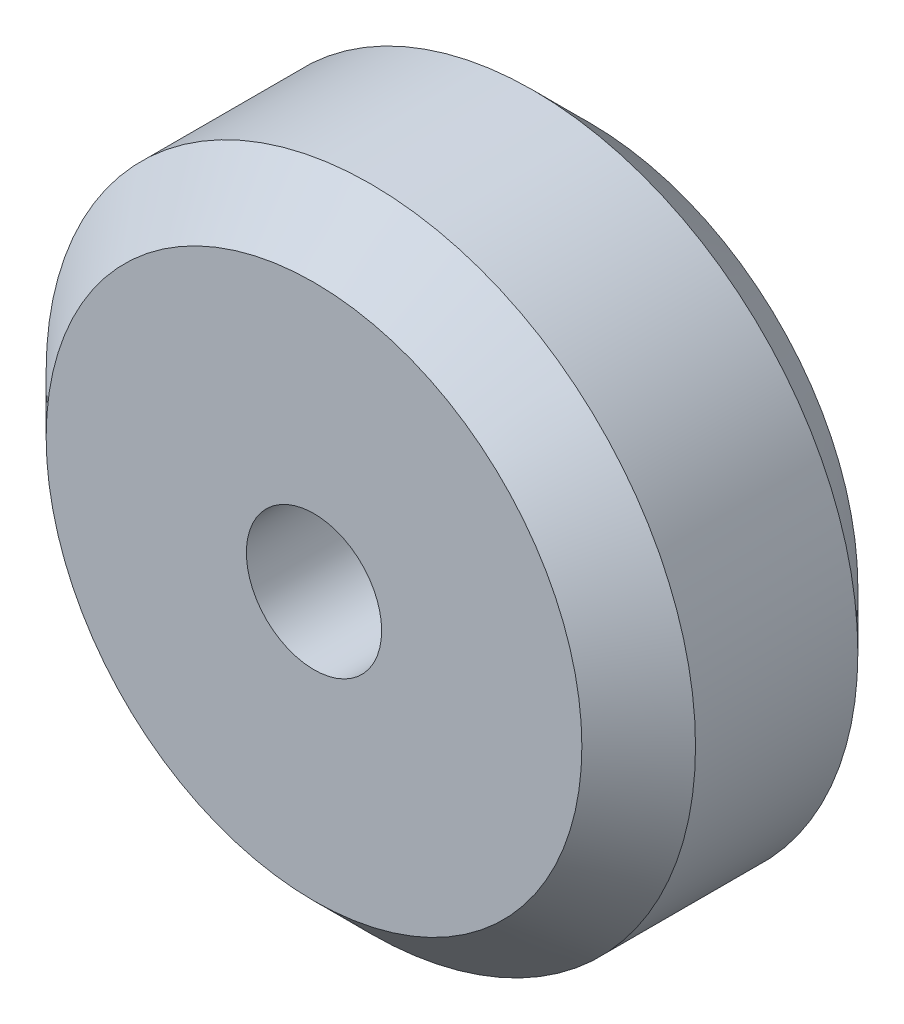
SolidWorks part; units mm, degrees
ref_plane "Front Plane" through (0, 0, 0) normal (0, 0, 1) x (1, 0, 0)
ref_plane "Top Plane" through (0, 0, 0) normal (0, 1, 0) x (1, 0, 0)
ref_plane "Right Plane" through (0, 0, 0) normal (1, 0, 0) x (0, 0, -1)
sketch "Sketch2" plane through (0, 0, 0) normal (0, 0, 1) x (1, 0, 0)
  circle A0 centre (0, 0) radius 12
  circle A1 centre (0, 0) radius 2.5
  dimension "D1" = 24
  dimension "D2" = 5
extrude "Boss-Extrude1" add sketch "Sketch2" along normal blind 10.2
chamfer "Chamfer1" distance 2.1 angle 45 2 edges at (12, 0, 0) (12, 0, 10.2)
